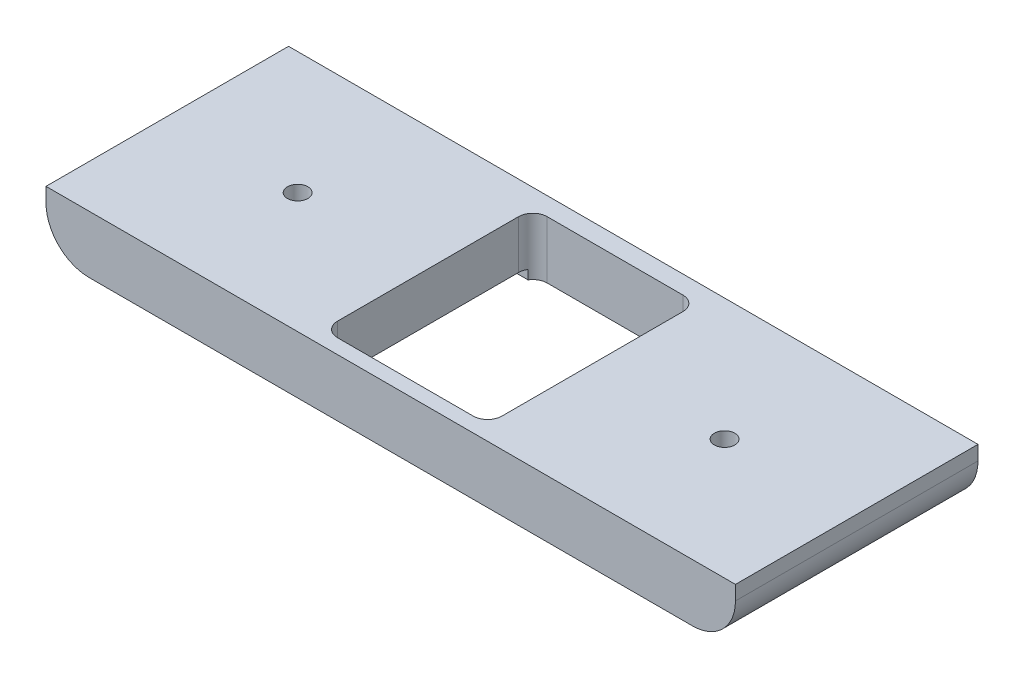
SolidWorks part; units mm, degrees
material "1060 Alloy"
ref_plane "Front Plane" through (0, 0, 0) normal (0, 0, 1) x (1, 0, 0)
ref_plane "Top Plane" through (0, 0, 0) normal (0, 1, 0) x (1, 0, 0)
ref_plane "Right Plane" through (0, 0, 0) normal (1, 0, 0) x (0, 0, -1)
sketch "Sketch1" plane through (0, 0, 0) normal (0, 1, 0) x (1, 0, 0)
  line L1 (-58.9313, 20.2988) -> (17.2687, 20.2988)
  line L2 (-58.9313, 20.2988) -> (-58.9313, -6.5105)
  line L3 (-58.9313, -6.5105) -> (17.2687, -6.5105)
  line L4 (17.2687, 20.2988) -> (17.2687, -6.5105)
  line L6 (17.2687, -4.1293) -> (17.2687, 17.5207) construction
  line L8 (-102.98, -7.3043) -> (-57.98, -7.3043) construction
  point P0 (0, 0)
  dimension "D1" = 0.7937
extrude "Boss-Extrude1" add sketch "Sketch1" along normal blind 6.35
fillet "Fillet1" radius 4.7625 2 edges at (17.2687, 0, -6.8941) (-58.9313, 0, -6.8941)
sketch "Sketch2" plane through (17.2687, 0, 0) normal (1, 0, 0) x (0, 0, -1)
  line L0 (-4.1293, 0) -> (-4.1293, 1)
  line L1 (-6.5105, 0) -> (20.2988, 0) construction
  line L2 (-4.1293, 1) -> (17.5207, 1)
  line L3 (17.5207, 1) -> (17.5207, 0)
  line L4 (17.5207, -1.2) -> (17.5207, -0.2) construction
  line L5 (-4.1293, -1.2) -> (17.5207, -1.2) construction
  line L6 (-4.1293, -1.2) -> (-4.1293, -0.2) construction
  line L7 (-4.1293, 0) -> (17.5207, 0)
extrude "Cut-Extrude1" cut sketch "Sketch2" against normal through all
sketch "Sketch3" plane through (0, 1, 0) normal (0, -1, 0) x (1, 0, 0)
  line L0 (-11.7438, 3.3043) -> (-11.7438, -16.6957) construction
  line L1 (-13.3313, -18.2832) -> (-28.3313, -18.2832) construction
  line L2 (-29.9188, -16.6957) -> (-29.9188, 3.3043) construction
  line L3 (-28.3313, 4.8918) -> (-13.3313, 4.8918) construction
  line L4 (-11.7438, 3.3043) -> (-11.7438, -16.6957)
  line L5 (-13.3313, -18.2832) -> (-28.3313, -18.2832)
  line L6 (-29.9188, -16.6957) -> (-29.9188, 3.3043)
  line L7 (-28.3313, 4.8918) -> (-13.3313, 4.8918)
  arc A1 (-13.3313, -18.2832) -> (-11.7438, -16.6957) centre (-13.3313, -16.6957) ccw construction
  arc A2 (-29.9188, -16.6957) -> (-28.3313, -18.2832) centre (-28.3313, -16.6957) ccw construction
  arc A3 (-28.3313, 4.8918) -> (-29.9188, 3.3043) centre (-28.3313, 3.3043) ccw construction
  arc A4 (-11.7438, 3.3043) -> (-13.3313, 4.8918) centre (-13.3313, 3.3043) ccw construction
  arc A5 (-13.3313, -18.2832) -> (-11.7438, -16.6957) centre (-13.3313, -16.6957) ccw
  arc A6 (-29.9188, -16.6957) -> (-28.3313, -18.2832) centre (-28.3313, -16.6957) ccw
  arc A7 (-28.3313, 4.8918) -> (-29.9188, 3.3043) centre (-28.3313, 3.3043) ccw
  arc A8 (-11.7438, 3.3043) -> (-13.3313, 4.8918) centre (-13.3313, 3.3043) ccw
extrude "Cut-Extrude2" cut sketch "Sketch3" against normal through all and the other way through all
hole_wizard "#4-40 Tapped Hole1" positions "Sketch5" profile "Sketch4" tap size "#4-40" standard "Ansi Inch" end condition through all
sketch "Sketch5" plane through (0, 6.35, 0) normal (0, 1, 0) x (-1, 0, 0)
  line L0 (29.9188, -6.6957) -> (58.9313, -6.8941) construction
  line L1 (29.9188, 3.3043) -> (29.9188, -16.6957) construction
  line L2 (58.9313, -20.2988) -> (58.9313, 6.5105) construction
  line L4 (20.8313, -20.2988) -> (20.8313, 6.5105) construction
  line L5 (-17.2687, -20.2988) -> (58.9313, -20.2988) construction
  line L6 (58.9313, 6.5105) -> (-17.2687, 6.5105) construction
  point P1 (44.4251, -6.7949)
  point P25 (-2.7624, -6.7949)
cosmetic thread "Hole Thread1" parameters "D2"=2.8448
cosmetic thread "Hole Thread2" parameters "D2"=2.8448
sketch "Sketch4" plane through (-44.4251, 6.35, -6.7949) normal (1, 0, 0) x (0, 0, 1)
  line L0 (0, 0) -> (0, 6.35)
  line L1 (0, 6.35) -> (1.1303, 6.35)
  line L2 (1.1303, 6.35) -> (1.1303, 0)
  line L5 (1.1303, 0) -> (0, 0)
  line L11 (0, -6.35) -> (0, 107.95) construction
  dimension "Thru Tap Drill Dia." = 2.2606
  dimension "Thru Tap Drill Depth" = 6.35
